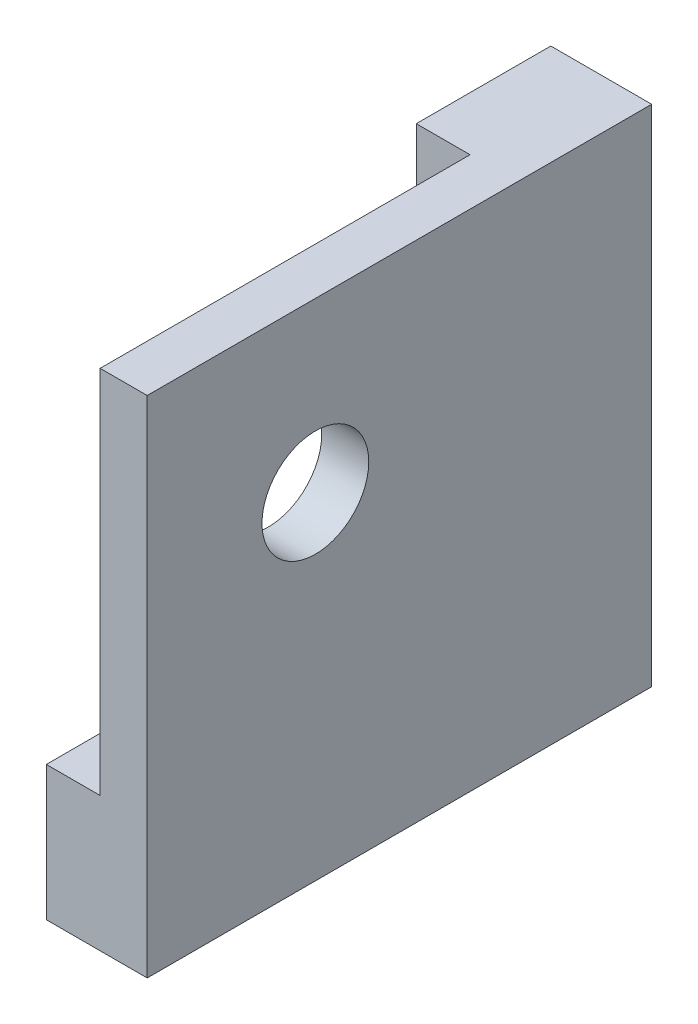
SolidWorks part; units mm, degrees
ref_plane "Front Plane" through (0, 0, 0) normal (0, 0, 1) x (1, 0, 0)
ref_plane "Top Plane" through (0, 0, 0) normal (0, 1, 0) x (1, 0, 0)
ref_plane "Right Plane" through (0, 0, 0) normal (1, 0, 0) x (0, 0, -1)
sketch "Sketch2" plane through (0, 0, 0) normal (1, 0, 0) x (0, 0, -1)
  line L0 (0, 0) -> (30, 0)
  line L2 (0, 0) -> (0, -30)
  line L5 (30, -30) -> (0, -30)
  line L6 (30, -30) -> (30, 0)
  circle A0 centre (10, -10) radius 3.175
  dimension "D4" = 6.35
  dimension "D1" = 30
  dimension "D3" = 30
  dimension "D5" = 10
  dimension "D6" = 10
extrude "Boss-Extrude1" add sketch "Sketch2" along normal blind 6 contours L5 L6 L0 L2 A0
sketch "Sketch3" plane through (0, 0, 0) normal (-1, 0, 0) x (0, 0, 1)
  line L0 (0, 0) -> (0, -30) construction
  line L1 (-22, -10) -> (-22, 0)
  line L2 (0, 0) -> (-30, 0) construction
  line L3 (-10, -22) -> (0, -22)
  arc A0 (-22, -10) -> (-10, -22) centre (-10, -10) ccw
  point P1 (0, -20)
  dimension "D1" = 12
extrude "Cut-Extrude1" cut sketch "Sketch3" against normal blind 3.2 and the other way through all
